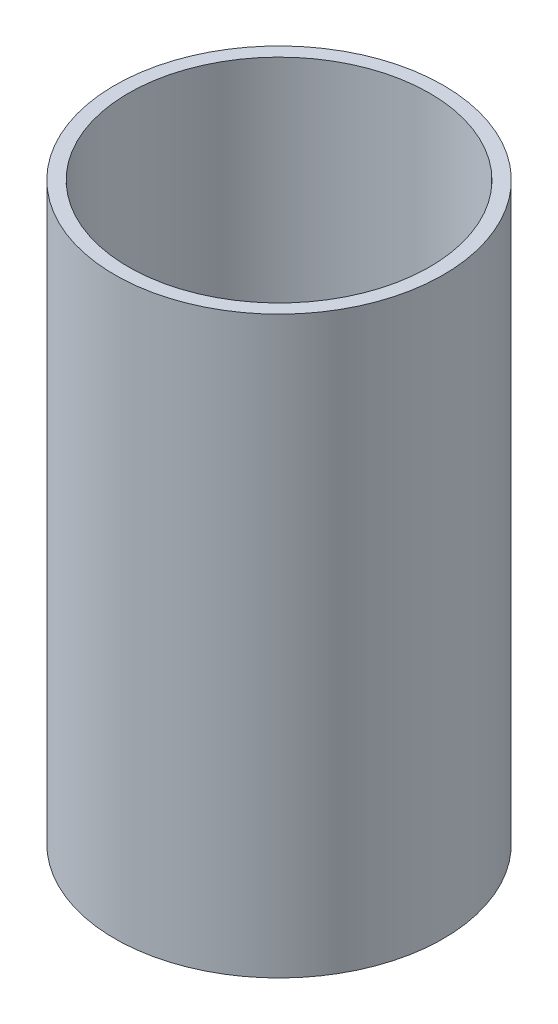
SolidWorks part; units mm, degrees
ref_plane "Front Plane" through (0, 0, 0) normal (0, 0, 1) x (1, 0, 0)
ref_plane "Top Plane" through (0, 0, 0) normal (0, 1, 0) x (1, 0, 0)
ref_plane "Right Plane" through (0, 0, 0) normal (1, 0, 0) x (0, 0, -1)
sketch "Sketch1" plane through (0, 0, 0) normal (0, 1, 0) x (1, 0, 0)
  circle A0 centre (0, 0) radius 12
  circle A1 centre (0, 0) radius 11
  dimension "D1" = 24
  dimension "D2" = 22
extrude "Boss-Extrude1" add sketch "Sketch1" along normal blind 42
